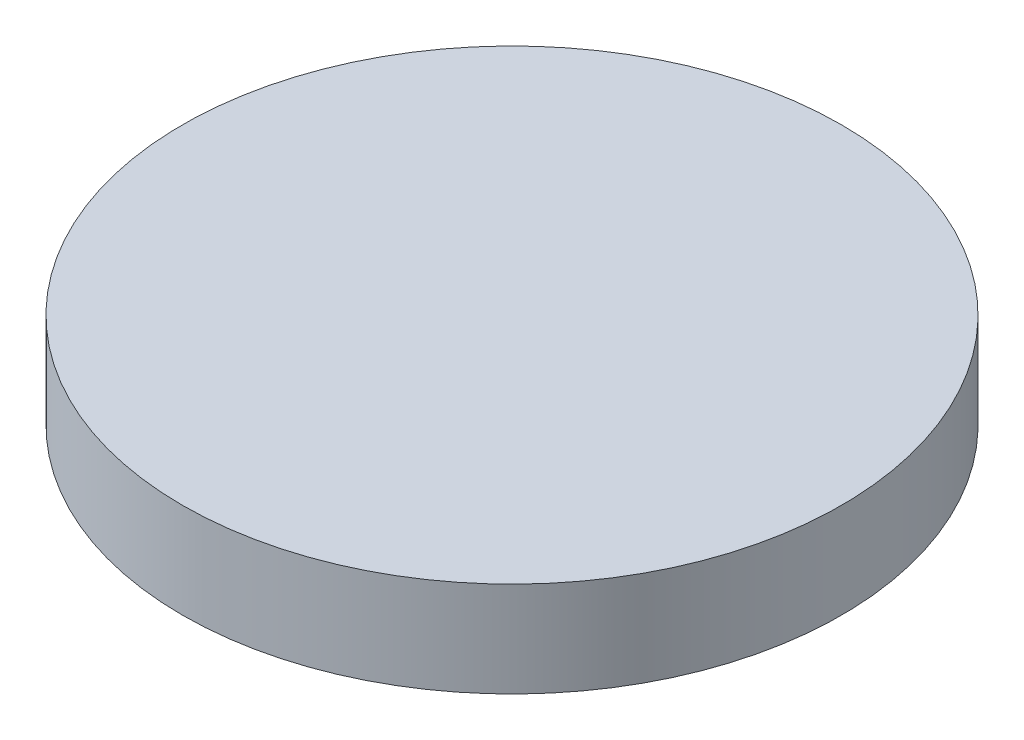
SolidWorks part; units mm, degrees
ref_plane "Front" through (0, 0, 0) normal (0, 0, 1) x (1, 0, 0)
ref_plane "Top" through (0, 0, 0) normal (0, 1, 0) x (1, 0, 0)
ref_plane "Right" through (0, 0, 0) normal (1, 0, 0) x (0, 0, -1)
sketch "Sketch1" plane through (0, 0, 0) normal (0, 1, 0) x (1, 0, 0)
  circle A0 centre (0, 0) radius 34.6329
extrude "Boss-Extrude1" add sketch "Sketch1" along normal blind 10
